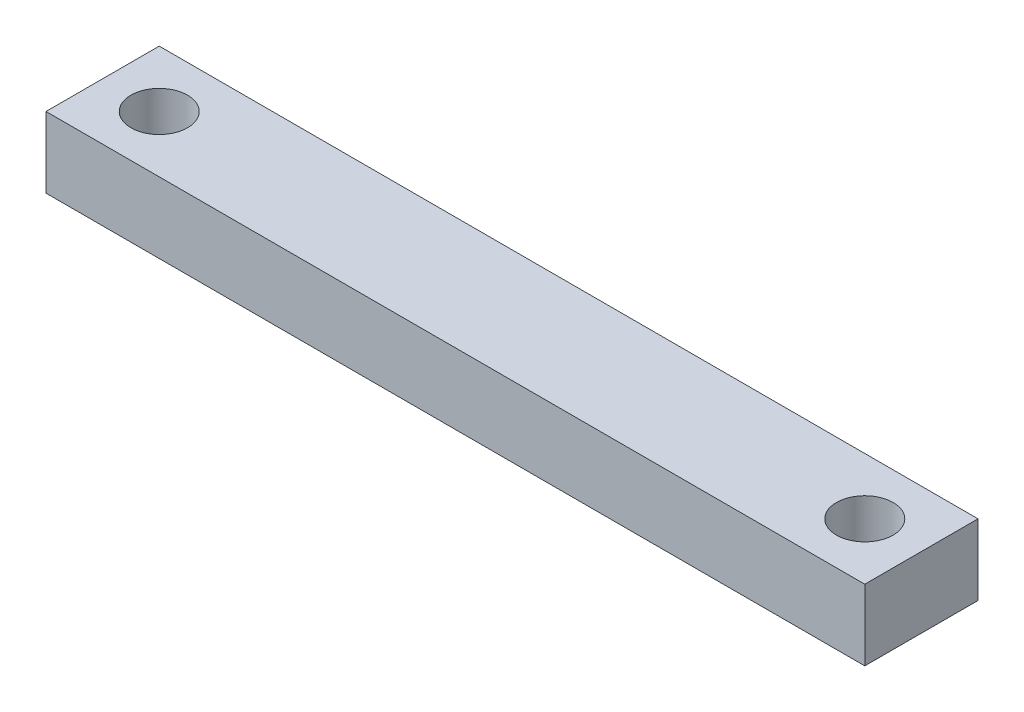
SolidWorks part; units mm, degrees
ref_plane "Front Plane" through (0, 0, 0) normal (0, 0, 1) x (1, 0, 0)
ref_plane "Top Plane" through (0, 0, 0) normal (0, 1, 0) x (1, 0, 0)
ref_plane "Right Plane" through (0, 0, 0) normal (1, 0, 0) x (0, 0, -1)
sketch "Sketch1" plane through (0, 0, 0) normal (0, 1, 0) x (1, 0, 0)
  line L1 (0, 0) -> (57.85, 0)
  line L2 (0, 0) -> (0, 8)
  line L3 (0, 8) -> (57.85, 8)
  line L4 (57.85, 0) -> (57.85, 8)
  circle A0 centre (4, 4) radius 2
  circle A1 centre (53.85, 4) radius 2
  dimension "D3" = 4
  dimension "D4" = 4
  dimension "D1" = 57.85
  dimension "D2" = 8
  dimension "D5" = 4
  dimension "D6" = 4
  dimension "D7" = 4
  dimension "D8" = 4
extrude "Boss-Extrude1" add sketch "Sketch1" along normal blind 5
